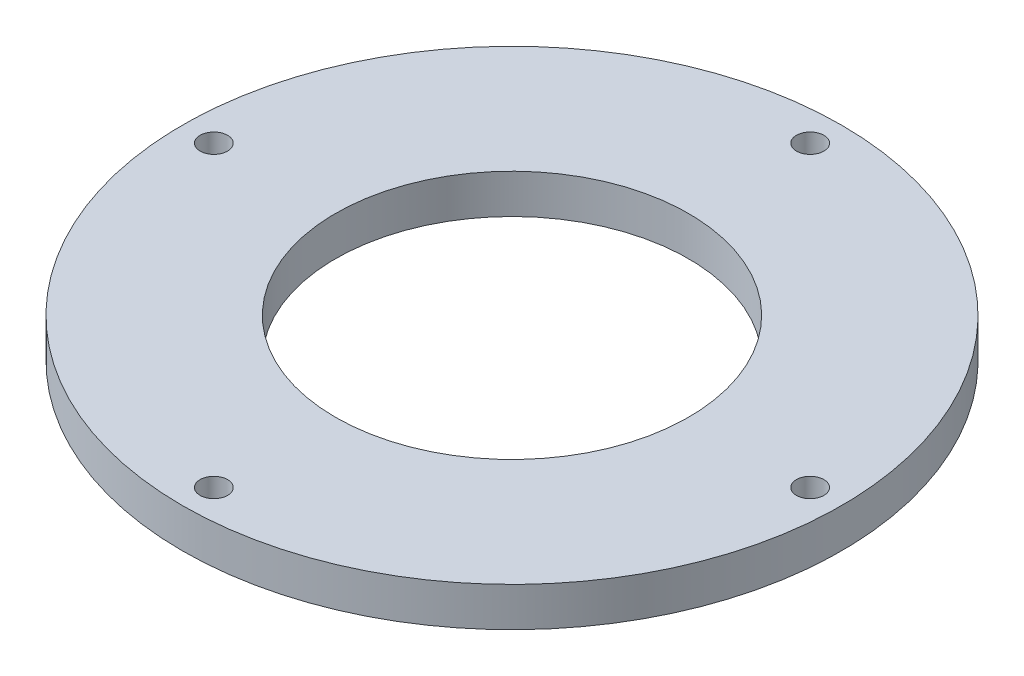
SolidWorks part; units mm, degrees
ref_plane "Front Plane" through (0, 0, 0) normal (0, 0, 1) x (1, 0, 0)
ref_plane "Top Plane" through (0, 0, 0) normal (0, 1, 0) x (1, 0, 0)
ref_plane "Right Plane" through (0, 0, 0) normal (1, 0, 0) x (0, 0, -1)
sketch "Sketch1" plane through (0, 0, 0) normal (0, 1, 0) x (1, 0, 0)
  circle A0 centre (0, 0) radius 84
  circle A1 centre (0, 0) radius 45
  dimension "D1" = 168
  dimension "D2" = 90
extrude "Boss-Extrude1" add sketch "Sketch1" along normal blind 10
sketch "Sketch2" plane through (0, 10, 0) normal (0, 1, 0) x (1, 0, 0)
  circle A0 centre (0, 0) radius 76
  circle A1 centre (0, 76) radius 4.5903
  circle A2 centre (-76, 0) radius 3.7663
  circle A3 centre (76, 0) radius 3.517
  circle A4 centre (0, -76) radius 3.0544
  dimension "D1" = 152
hole_wizard "M6 Clearance Hole1" positions "3DSketch1" profile "Sketch3" hole size "M6" standard "ISO" end condition through all
sketch3d "3DSketch1"
  point P0 (-76, 10, 0)
  point P3 (0, 10, -76)
  point P6 (76, 10, 0)
  point P9 (0, 10, 76)
sketch "Sketch3" plane through (-76, 10, 0) normal (1, 0, 0) x (0, 0, 1)
  line L0 (0, 0) -> (0, 10)
  line L1 (0, 10) -> (3.5, 10)
  line L2 (3.5, 10) -> (3.5, 0)
  line L5 (3.5, 0) -> (0, 0)
  line L11 (0, -6.35) -> (0, 107.95) construction
  dimension "Thru Hole Dia." = 7
  dimension "Thru Hole Depth" = 10
